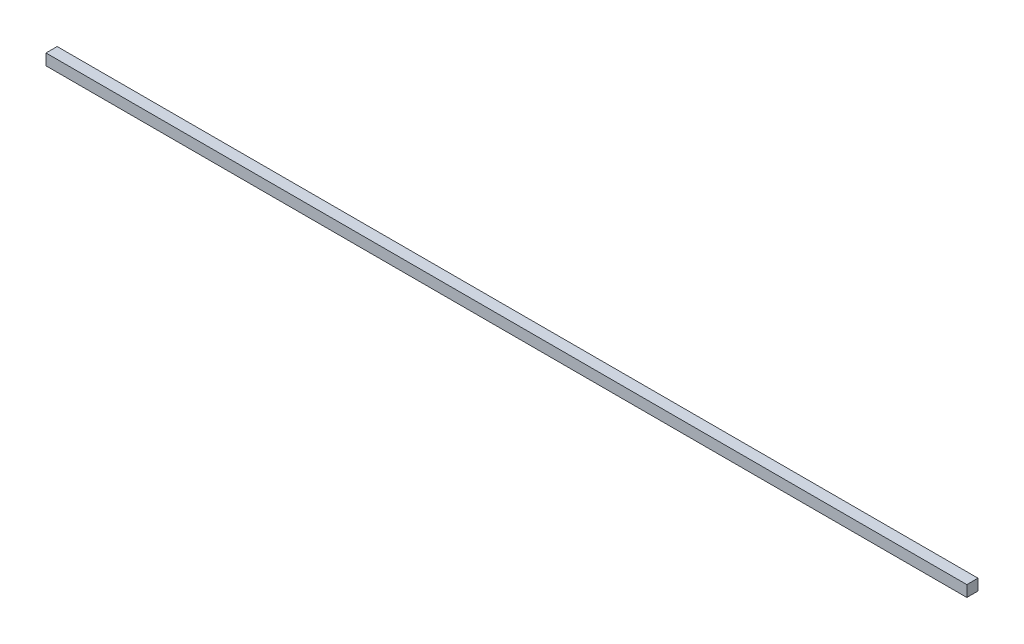
SolidWorks part; units mm, degrees
material "Balsa"
ref_plane "Front" through (0, 0, 0) normal (0, 0, 1) x (1, 0, 0)
ref_plane "Top" through (0, 0, 0) normal (0, 1, 0) x (1, 0, 0)
ref_plane "Right" through (0, 0, 0) normal (1, 0, 0) x (0, 0, -1)
sketch "Sketch1" plane through (1.5875, 0, 0) normal (1, 0, 0) x (0, 0, -1)
  line L0 (612.9211, 24.0273) -> (612.9211, -25.8118) construction
  line L1 (612.9211, 21.7243) -> (609.7461, 21.7243)
  line L2 (612.9211, 21.7243) -> (612.9211, 18.5493)
  line L3 (612.9211, 18.5493) -> (609.7461, 18.5493)
  line L4 (609.7461, 21.7243) -> (609.7461, 18.5493)
  line L5 (616.0961, 24.8993) -> (612.9211, 24.8993) construction
  line L6 (616.0961, 24.8993) -> (612.9211, 24.8993)
  dimension "D1" = 3.175
  dimension "D2" = 3.175
  dimension "D3" = 3.175
extrude "Boss-Extrude1" add sketch "Sketch1" along normal up to surface (261.9375 mm away) contours L1 L4 L3 L2
